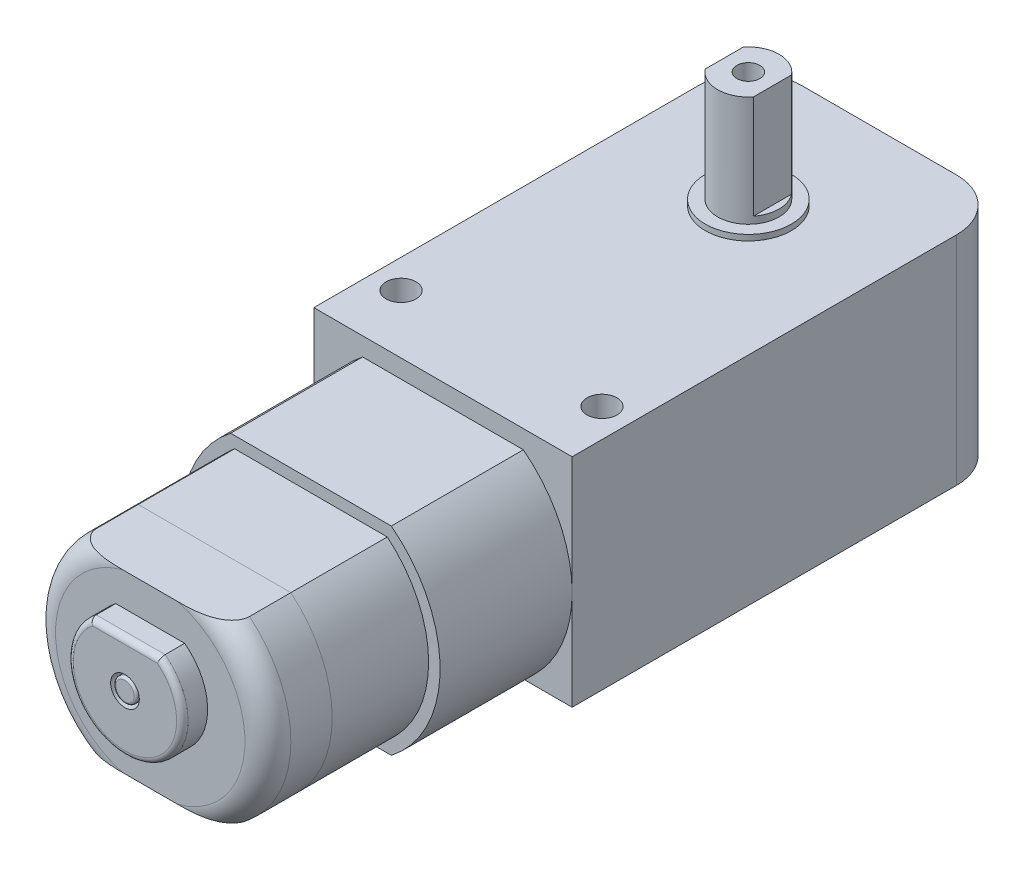
SolidWorks part; units mm, degrees
ref_plane "Front Plane" through (0, 0, 0) normal (0, 0, 1) x (1, 0, 0)
ref_plane "Top Plane" through (0, 0, 0) normal (0, 1, 0) x (1, 0, 0)
ref_plane "Right Plane" through (0, 0, 0) normal (1, 0, 0) x (0, 0, -1)
sketch "Sketch1" plane through (0, 0, 0) normal (0, 1, 0) x (1, 0, 0)
  line L1 (11.25, 19) -> (-11.25, 19)
  line L2 (11.25, 19) -> (11.25, -19)
  line L3 (11.25, -19) -> (-11.25, -19)
  line L4 (-11.25, 19) -> (-11.25, -19)
  line L5 (11.25, 19) -> (-11.25, -19) construction
  line L6 (11.25, -19) -> (-11.25, 19) construction
  point P0 (0, 0)
  dimension "D1" = 22.5
  dimension "D2" = 38
extrude "Boss-Extrude1" add sketch "Sketch1" along normal mid plane 18.9
fillet "Fillet1" radius 4.5 2 edges at (-11.25, 0, -19) (11.25, 0, -19)
sketch "Sketch2" plane through (0, 0, 19) normal (0, 0, 1) x (1, 0, 0)
  line L0 (-11.25, -9.45) -> (11.25, -9.45) construction
  line L5 (7, -9.45) -> (-7, -9.45)
  line L7 (7, 7.85) -> (-7, 7.85)
  line L9 (7, -9.45) -> (-7, 7.85) construction
  line L10 (7, 7.85) -> (-7, -9.45) construction
  line L13 (-11.25, 9.45) -> (-11.25, -9.45) construction
  arc A0 (-7, 7.85) -> (-7, -9.45) centre (-0.3224, -0.8) ccw
  arc A1 (7, 7.85) -> (7, -9.45) centre (0.3224, -0.8) cw
  point P0 (0, -0.8)
  dimension "D3" = 10.9276
  dimension "D1" = 17.3
  dimension "D2" = 14
extrude "Boss-Extrude2" add sketch "Sketch2" along normal blind 11.5
sketch "Sketch3" plane through (0, 0, 30.5) normal (0, 0, 1) x (1, 0, 0)
  line L4 (-6.6497, -8.45) -> (6.6497, -8.45)
  line L5 (6.6497, 6.85) -> (-6.6497, 6.85)
  line L6 (-6.6497, -8.45) -> (6.6497, -8.45)
  line L7 (6.6497, 6.85) -> (-6.6497, 6.85)
  arc A4 (-6.6497, 6.85) -> (-6.6497, -8.45) centre (-0.3224, -0.8) ccw
  arc A5 (6.6497, -8.45) -> (6.6497, 6.85) centre (0.3224, -0.8) ccw
  arc A6 (-6.6497, 6.85) -> (-6.6497, -8.45) centre (-0.3224, -0.8) ccw
  arc A7 (6.6497, -8.45) -> (6.6497, 6.85) centre (0.3224, -0.8) ccw
  dimension "D1" = 1
extrude "Cut-Extrude1" cut sketch "Sketch3" against normal up to surface (11.5 mm away) up to face at (0, 5.6646, 19)
sketch "Sketch4" plane through (0, 0, 0) normal (0, 1, 0) x (1, 0, 0)
  line L0 (6.75, 19) -> (-6.75, 19) construction
  line L1 (2.5, 19) -> (-2.5, 19)
  line L2 (2.5, 19) -> (2.5, 24)
  line L3 (2.5, 24) -> (-2.5, 24)
  line L4 (-2.5, 19) -> (-2.5, 24)
  line L5 (2.5, 19) -> (-2.5, 24) construction
  line L6 (2.5, 24) -> (-2.5, 19) construction
  circle A0 centre (0, 21.5) radius 1.25
  point P0 (0, 21.5)
  dimension "D3" = 2.5
  dimension "D1" = 5
  dimension "D2" = 5
extrude "Boss-Extrude3" add sketch "Sketch4" along normal mid plane 2.5 contours L4 L1 L2 L3 A0
sketch "Sketch5" plane through (0, 9.45, 0) normal (0, 1, 0) x (1, 0, 0)
  line L0 (0, 24) -> (0, 0) construction
  line L1 (2.5, 24) -> (-2.5, 24) construction
  line L2 (6.75, 19) -> (-6.75, 19) construction
  circle A0 centre (0, 7.6) radius 3.75
  dimension "D1" = 7.5
  dimension "D2" = 11.4
extrude "Boss-Extrude4" add sketch "Sketch5" along normal blind 0.5
sketch "Sketch6" plane through (0, 9.95, 0) normal (0, 1, 0) x (1, 0, 0)
  circle A0 centre (0, 7.6) radius 2.675
  dimension "D1" = 5.35
extrude "Boss-Extrude5" add sketch "Sketch6" along normal blind 9.6
sketch "Sketch7" plane through (0, 19.55, 0) normal (0, 1, 0) x (1, 0, 0)
  line L0 (-2.1, 9.257) -> (-2.1, 5.943)
  line L1 (2.1, 9.257) -> (2.1, 5.943)
  line L2 (-2.1, 7.6) -> (2.1, 7.6) construction
  circle A0 centre (0, 7.6) radius 2.675 construction
  circle A1 centre (0, 7.6) radius 2.675 construction
  arc A2 (2.1, 5.943) -> (2.1, 9.257) centre (0, 7.6) ccw
  circle A3 centre (0, 7.6) radius 2.675
  arc A4 (-2.1, 9.257) -> (-2.1, 5.943) centre (0, 7.6) ccw
  point P10 (0, 7.6)
  dimension "D2" = 4.2
  dimension "D1" = 0
extrude "Cut-Extrude4" cut sketch "Sketch7" against normal blind 9
sketch "Sketch8" plane through (0, 19.55, 0) normal (0, 1, 0) x (1, 0, 0)
  circle A0 centre (0, 7.6) radius 1
  dimension "D1" = 2
extrude "Cut-Extrude5" cut sketch "Sketch8" against normal up to surface (9 mm away) up to face at (-2.3875, 10.55, -7.6)
fillet "Fillet2" radius 0.5 2 edges at (2.5, 0, -24) (-2.5, 0, -24)
sketch "Sketch9" plane through (0, 0, 19) normal (0, 0, 1) x (1, 0, 0)
  line L2 (-6.6497, -8.45) -> (6.6497, -8.45)
  line L3 (6.6497, 6.85) -> (-6.6497, 6.85)
  line L4 (-6.6497, -8.45) -> (6.6497, -8.45)
  line L5 (6.6497, 6.85) -> (-6.6497, 6.85)
  arc A2 (-6.6497, 6.85) -> (-6.6497, -8.45) centre (-0.3224, -0.8) ccw
  arc A3 (6.6497, -8.45) -> (6.6497, 6.85) centre (0.3224, -0.8) ccw
  arc A4 (-6.6497, 6.85) -> (-6.6497, -8.45) centre (-0.3224, -0.8) ccw
  arc A5 (6.6497, -8.45) -> (6.6497, 6.85) centre (0.3224, -0.8) ccw
  dimension "D1" = 0
extrude "Boss-Extrude6" add sketch "Sketch9" along normal blind 27.7 separate body
sketch "Sketch10" plane through (0, 6.85, 0) normal (0, 1, 0) x (1, 0, 0)
  line L0 (-10.25, -38.9) -> (10.25, -38.9)
  line L1 (-10.25, -19) -> (-10.25, -46.7) construction
  line L2 (10.25, -46.7) -> (10.25, -19) construction
  line L3 (7, -30.5) -> (-7, -30.5) construction
  dimension "D1" = 8.4
split "Split1" trim tools "Sketch10" bodies to split 109 resulting bodies 110 111
sketch "Sketch11" plane through (0, 0, 46.7) normal (0, 0, 1) x (1, 0, 0)
  line L0 (-3, 4) -> (3, 4)
  line L3 (-6.6497, -8.45) -> (6.6497, -8.45)
  line L4 (6.6497, 6.85) -> (-6.6497, 6.85)
  line L5 (-6.6497, -8.45) -> (6.6497, -8.45)
  line L6 (6.6497, 6.85) -> (-6.6497, 6.85)
  arc A0 (-3, 4) -> (3, 4) centre (0, 0) ccw
  arc A3 (-6.6497, 6.85) -> (-6.6497, -8.45) centre (-0.3224, -0.8) ccw
  arc A7 (-6.6497, 6.85) -> (-6.6497, -8.45) centre (-0.3224, -0.8) ccw
  arc A9 (6.6497, -8.45) -> (6.6497, 6.85) centre (0.3224, -0.8) ccw
  arc A10 (6.6497, -8.45) -> (6.6497, 6.85) centre (0.3224, -0.8) ccw
  dimension "D1" = 10
  dimension "D2" = 9
  dimension "D3" = 0
extrude "Cut-Extrude6" cut sketch "Sketch11" against normal blind 2.2
fillet "Fillet4" radius 0.5 2 edges at (0, -5, 46.7) (0, 4, 46.7)
fillet "Fillet3" radius 2 2 edges at (-10.25, -0.8, 44.5) (10.25, -0.8, 44.5)
sketch "Sketch12" plane through (0, 0, 46.7) normal (0, 0, 1) x (1, 0, 0)
  circle A0 centre (0, 0) radius 1.25
  dimension "D1" = 2.5
extrude "Cut-Extrude7" cut sketch "Sketch12" against normal up to surface (2.2 mm away) up to face at (0, -0.5, 44.5)
sketch "Sketch13" plane through (0, 0, 44.5) normal (0, 0, 1) x (1, 0, 0)
  circle A0 centre (0, 0) radius 1
  dimension "D1" = 2
extrude "Boss-Extrude7" add sketch "Sketch13" along normal up to surface (2.2 mm away) up to face at (1.25, 0, 46.7)
fillet "Fillet5" radius 0.2 1 edges at (1, 0, 46.7)
sketch "Sketch14" plane through (0, 9.45, 0) normal (0, 1, 0) x (1, 0, 0)
  line L0 (-8.75, -13.9) -> (8.75, -13.9) construction
  line L1 (11.25, -19) -> (11.25, 14.5) construction
  line L4 (7, -19) -> (11.25, -19) construction
  circle A0 centre (-8.75, -13.9) radius 1.3
  circle A1 centre (8.75, -13.9) radius 1.3
  point P11 (0, -13.9)
  dimension "D1" = 2.6
  dimension "D2" = 2.5
  dimension "D3" = 5.1
extrude "Cut-Extrude8" cut sketch "Sketch14" against normal up to surface (18.9 mm away) up to face at (0, -9.45, 6.8136)
equation "\"D2@Sketch14\"= 1.2 + (\"D1@Sketch14\"/2)"
equation "\"D3@Sketch14\"=3.8 + (\"D1@Sketch14\"/2)"
